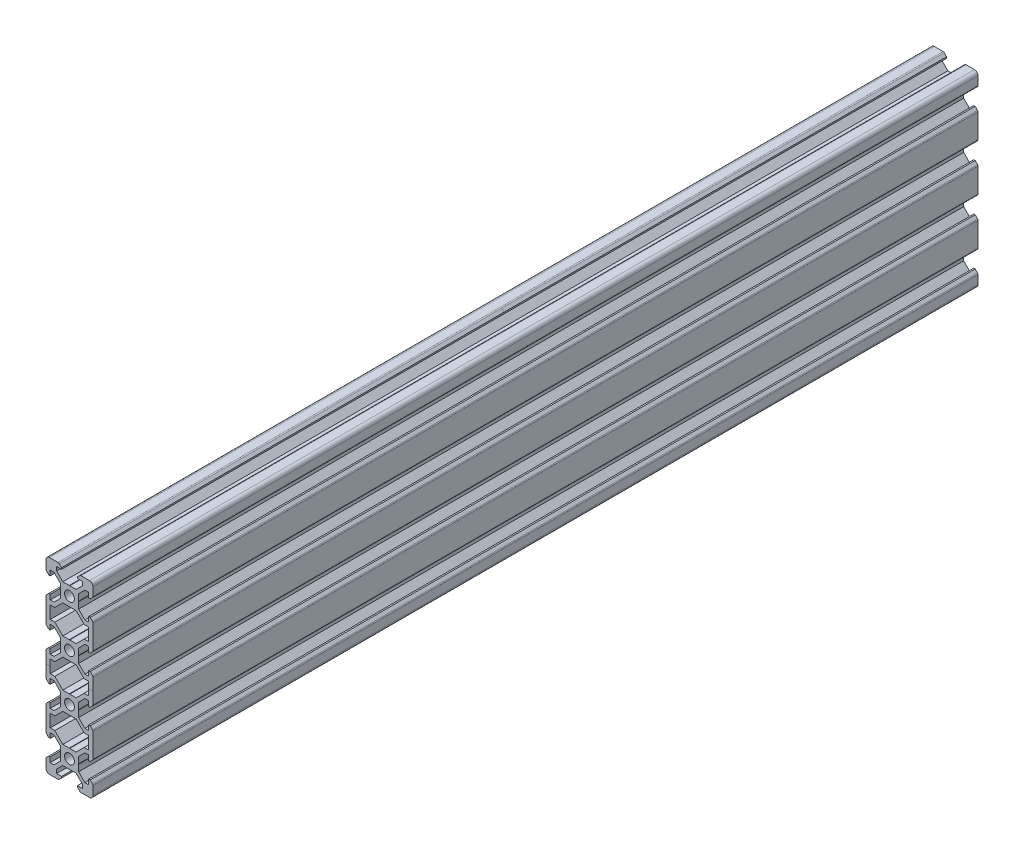
SolidWorks part; units mm, degrees
material "6063-T5"
ref_plane "Front" through (0, 0, 0) normal (0, 0, 1) x (1, 0, 0)
ref_plane "Top" through (0, 0, 0) normal (0, 1, 0) x (1, 0, 0)
ref_plane "Right" through (0, 0, 0) normal (1, 0, 0) x (0, 0, -1)
sketch "Sketch1" plane through (0, 0, 0) normal (0, 0, 1) x (1, 0, 0)
  line L0 (-8.5, 10) -> (-10, 8.5) construction
  line L1 (-8.5, 10) -> (-4.8628, 10)
  line L2 (-10, 8.5) -> (-10, 4.8628)
  line L3 (25.9287, -20) -> (-28.3599, -20) construction
  line L4 (10, 8.5) -> (10, 4.8628)
  line L5 (-10, 10) -> (10, -10) construction
  line L6 (-10, -10) -> (10, 10) construction
  line L7 (8.2, -5.5) -> (8.2, -3.3865)
  line L8 (-8.2, -5.5) -> (-8.2, -3.3865)
  line L9 (-5.5, 8.2) -> (-3.3865, 8.2)
  line L10 (-8.2, -12.7) -> (-8.2, -7.3)
  line L11 (-3.9005, 2.8395) -> (-6.561, 5.5)
  line L12 (-6.561, 5.5) -> (-8.2, 5.5)
  line L13 (-2.8395, -3.9005) -> (-0.1, -3.9005)
  line L14 (-3.9005, -2.8395) -> (-3.9005, -0.1)
  line L15 (-2.8395, 3.9005) -> (-0.1, 3.9005)
  line L16 (3.9005, -2.8395) -> (3.9005, -0.1)
  line L17 (-8.2, 3.3865) -> (-8.81, 3.3865)
  line L18 (-8.81, 3.3865) -> (-9.7976, 4.3741)
  line L19 (8.5, 10) -> (10, 8.5) construction
  line L20 (-2.8395, 3.9005) -> (-5.5, 6.561)
  line L21 (-5.5, 6.561) -> (-5.5, 8.2)
  line L22 (-3.3865, 8.2) -> (-3.3865, 8.81)
  line L23 (-3.3865, 8.81) -> (-4.3741, 9.7976)
  line L24 (0, 24.069) -> (0, -33.8154) construction
  line L25 (3.3865, 8.81) -> (4.3741, 9.7976)
  line L26 (3.3865, 8.2) -> (3.3865, 8.81)
  line L27 (5.5, 6.561) -> (5.5, 8.2)
  line L28 (2.8395, 3.9005) -> (5.5, 6.561)
  line L29 (3.3865, 8.2) -> (5.5, 8.2)
  line L30 (4.8628, 10) -> (8.5, 10)
  line L31 (-0.1, 3.9005) -> (0, 3.8005)
  line L32 (0.1, 3.9005) -> (0, 3.8005)
  line L33 (0.1, 3.9005) -> (2.8395, 3.9005)
  line L34 (25.9287, 0) -> (-28.3459, 0) construction
  line L35 (-0.1, -3.9005) -> (0, -3.8005)
  line L36 (0.1, -3.9005) -> (0, -3.8005)
  line L37 (0.1, -3.9005) -> (2.8395, -3.9005)
  line L38 (-3.9005, 0.1) -> (-3.8005, 0)
  line L39 (-3.8005, 0) -> (-3.9005, -0.1)
  line L40 (-3.9005, 0.1) -> (-3.9005, 2.8395)
  line L41 (3.9005, 0.1) -> (3.8005, 0)
  line L42 (3.8005, 0) -> (3.9005, -0.1)
  line L43 (3.9005, 0.1) -> (3.9005, 2.8395)
  line L44 (8.81, 3.3865) -> (9.7976, 4.3741)
  line L45 (8.2, 3.3865) -> (8.81, 3.3865)
  line L46 (6.561, 5.5) -> (8.2, 5.5)
  line L47 (3.9005, 2.8395) -> (6.561, 5.5)
  line L48 (2.8395, -3.9005) -> (5.5, -6.561)
  line L49 (3.9005, -2.8395) -> (6.561, -5.5)
  line L50 (-2.8395, -3.9005) -> (-5.5, -6.561)
  line L51 (-3.9005, -2.8395) -> (-6.561, -5.5)
  line L52 (6.561, -5.5) -> (8.2, -5.5)
  line L53 (-6.561, -5.5) -> (-8.2, -5.5)
  line L54 (-8.81, -3.3865) -> (-9.7976, -4.3741)
  line L55 (-8.2, -3.3865) -> (-8.81, -3.3865)
  line L56 (8.81, -3.3865) -> (9.7976, -4.3741)
  line L57 (8.2, -3.3865) -> (8.81, -3.3865)
  line L58 (8.2, 3.3865) -> (8.2, 5.5)
  line L59 (10, -4.8628) -> (10, -15.1372)
  line L60 (-8.2, 3.3865) -> (-8.2, 5.5)
  line L61 (-10, -4.8628) -> (-10, -15.1372)
  line L62 (-28.3459, -10) -> (-10, -10) construction
  line L63 (-3.9005, -20.1) -> (-3.9005, -22.8395)
  line L64 (-3.9005, -20.1) -> (-3.8005, -20)
  line L65 (-3.8005, -20) -> (-3.9005, -19.9)
  line L66 (3.9005, -20.1) -> (3.9005, -22.8395)
  line L67 (3.9005, -20.1) -> (3.8005, -20)
  line L68 (3.8005, -20) -> (3.9005, -19.9)
  line L69 (6.561, -14.5) -> (8.2, -14.5)
  line L70 (3.9005, -17.1605) -> (6.561, -14.5)
  line L71 (3.9005, -17.1605) -> (3.9005, -19.9)
  line L72 (-3.9005, -17.1605) -> (-3.9005, -19.9)
  line L73 (-3.9005, -17.1605) -> (-6.561, -14.5)
  line L74 (-6.561, -14.5) -> (-8.2, -14.5)
  line L75 (-8.2, -16.6135) -> (-8.81, -16.6135)
  line L76 (-8.81, -16.6135) -> (-9.7976, -15.6259)
  line L77 (8.2, -16.6135) -> (8.81, -16.6135)
  line L78 (8.81, -16.6135) -> (9.7976, -15.6259)
  line L79 (-2.8395, -16.0995) -> (-5.5, -13.439)
  line L80 (-2.8395, -16.0995) -> (-0.1, -16.0995)
  line L81 (-0.1, -16.0995) -> (0, -16.1995)
  line L82 (0.1, -16.0995) -> (0, -16.1995)
  line L83 (0.1, -16.0995) -> (2.8395, -16.0995)
  line L84 (2.8395, -16.0995) -> (5.5, -13.439)
  line L85 (-8.2, -16.6135) -> (-8.2, -14.5)
  line L86 (8.2, -16.6135) -> (8.2, -14.5)
  line L87 (2.8395, -23.9005) -> (5.5, -26.561)
  line L88 (-2.8395, -23.9005) -> (-5.5, -26.561)
  line L89 (-0.1, -23.9005) -> (0, -23.8005)
  line L90 (0.1, -23.9005) -> (0, -23.8005)
  line L91 (0.1, -23.9005) -> (2.8395, -23.9005)
  line L92 (-2.8395, -23.9005) -> (-0.1, -23.9005)
  line L93 (-8.2, -23.3865) -> (-8.2, -25.5)
  line L94 (-8.2, -23.3865) -> (-8.81, -23.3865)
  line L95 (-8.81, -23.3865) -> (-9.7976, -24.3741)
  line L96 (8.2, -23.3865) -> (8.2, -25.5)
  line L97 (8.2, -23.3865) -> (8.81, -23.3865)
  line L98 (8.81, -23.3865) -> (9.7976, -24.3741)
  line L99 (8.2, -27.3) -> (8.2, -32.7)
  line L100 (10, -35.1372) -> (10, -24.8628)
  line L101 (-10, -35.1372) -> (-10, -24.8628)
  line L102 (-8.2, -27.3) -> (-8.2, -32.7)
  line L103 (3.9005, -22.8395) -> (6.561, -25.5)
  line L104 (-3.9005, -22.8395) -> (-6.561, -25.5)
  line L105 (6.239, -27.3) -> (8.2, -27.3)
  line L106 (-6.239, -27.3) -> (-8.2, -27.3)
  line L107 (-6.561, -25.5) -> (-8.2, -25.5)
  line L108 (6.561, -25.5) -> (8.2, -25.5)
  line L109 (5.5, -26.561) -> (6.239, -27.3)
  line L110 (-5.5, -26.561) -> (-6.239, -27.3)
  line L111 (8.2, -34.5) -> (8.2, -36.6135)
  line L112 (8.2, -36.6135) -> (8.81, -36.6135)
  line L113 (8.81, -36.6135) -> (9.7976, -35.6259)
  line L114 (-8.2, -34.5) -> (-8.2, -36.6135)
  line L115 (-6.239, -7.3) -> (-8.2, -7.3)
  line L116 (-5.5, -6.561) -> (-6.239, -7.3)
  line L117 (6.239, -7.3) -> (8.2, -7.3)
  line L118 (5.5, -6.561) -> (6.239, -7.3)
  line L119 (-6.239, -12.7) -> (-8.2, -12.7)
  line L120 (-5.5, -13.439) -> (-6.239, -12.7)
  line L121 (5.5, -13.439) -> (6.239, -12.7)
  line L122 (6.239, -12.7) -> (8.2, -12.7)
  line L123 (8.2, -12.7) -> (8.2, -7.3)
  line L124 (-8.2, -36.6135) -> (-8.81, -36.6135)
  line L125 (10, -10) -> (25.9287, -10) construction
  line L126 (-8.81, -36.6135) -> (-9.7976, -35.6259)
  line L127 (-0.1, -56.0995) -> (0, -56.1995)
  line L128 (-0.1, -36.0995) -> (0, -36.1995)
  line L129 (0.1, -36.0995) -> (0, -36.1995)
  line L130 (0.1, -36.0995) -> (2.8395, -36.0995)
  line L131 (-6.561, -34.5) -> (-8.2, -34.5)
  line L132 (6.561, -34.5) -> (8.2, -34.5)
  line L133 (6.239, -32.7) -> (8.2, -32.7)
  line L134 (-6.239, -32.7) -> (-8.2, -32.7)
  line L135 (-5.5, -33.439) -> (-6.239, -32.7)
  line L136 (5.5, -33.439) -> (6.239, -32.7)
  line L137 (-26.6965, -30) -> (27.5921, -30) construction
  line L138 (0.1, -56.0995) -> (0, -56.1995)
  line L139 (0.1, -56.0995) -> (2.8395, -56.0995)
  line L140 (-2.8395, -56.0995) -> (-0.1, -56.0995)
  line L141 (0, -60) -> (0, -71.7864) construction
  line L142 (-3.8005, -60) -> (-3.9005, -59.9)
  line L143 (-3.9005, -60.1) -> (-3.8005, -60)
  line L144 (10, -68.5) -> (10, -64.8628)
  line L145 (0.1, -63.9005) -> (0, -63.8005)
  line L146 (-0.1, -63.9005) -> (0, -63.8005)
  line L147 (-2.8395, -63.9005) -> (-0.1, -63.9005)
  line L148 (0.1, -63.9005) -> (2.8395, -63.9005)
  line L149 (3.9005, -60.1) -> (3.9005, -62.8395)
  line L150 (3.9005, -60.1) -> (3.8005, -60)
  line L151 (3.8005, -60) -> (3.9005, -59.9)
  line L152 (3.9005, -57.1605) -> (3.9005, -59.9)
  line L153 (4.8628, -70) -> (8.5, -70)
  line L154 (3.3865, -68.81) -> (4.3741, -69.7976)
  line L155 (3.3865, -68.2) -> (3.3865, -68.81)
  line L156 (3.3865, -68.2) -> (5.5, -68.2)
  line L157 (-0.1, -43.9005) -> (0, -43.8005)
  line L158 (0.1, -43.9005) -> (0, -43.8005)
  line L159 (-2.8395, -43.9005) -> (-0.1, -43.9005)
  line L160 (0.1, -43.9005) -> (2.8395, -43.9005)
  line L161 (3.9005, -40.1) -> (3.8005, -40)
  line L162 (3.8005, -40) -> (3.9005, -39.9)
  line L163 (3.9005, -37.1605) -> (3.9005, -39.9)
  line L164 (3.9005, -40.1) -> (3.9005, -42.8395)
  line L165 (-2.8395, -36.0995) -> (-0.1, -36.0995)
  line L166 (-2.8395, -43.9005) -> (-5.5, -46.561)
  line L167 (-3.9005, -37.1605) -> (-3.9005, -39.9)
  line L168 (-3.8005, -40) -> (-3.9005, -39.9)
  line L169 (-3.9005, -40.1) -> (-3.8005, -40)
  line L170 (-3.9005, -42.8395) -> (-6.561, -45.5)
  line L171 (2.8395, -43.9005) -> (5.5, -46.561)
  line L172 (3.9005, -42.8395) -> (6.561, -45.5)
  line L173 (3.9005, -37.1605) -> (6.561, -34.5)
  line L174 (2.8395, -36.0995) -> (5.5, -33.439)
  line L175 (-3.9005, -42.8395) -> (-3.9005, -40.1)
  line L176 (-6.561, -34.5) -> (-3.9005, -37.1605)
  line L177 (-5.5, -33.439) -> (-2.8395, -36.0995)
  line L178 (5.5, -66.561) -> (5.5, -68.2)
  line L179 (6.561, -65.5) -> (8.2, -65.5)
  line L180 (8.2, -63.3865) -> (8.2, -65.5)
  line L181 (8.81, -63.3865) -> (9.7976, -64.3741)
  line L182 (8.2, -63.3865) -> (8.81, -63.3865)
  line L183 (-8.2, -63.3865) -> (-8.81, -63.3865)
  line L184 (-8.81, -63.3865) -> (-9.7976, -64.3741)
  line L185 (-8.2, -63.3865) -> (-8.2, -65.5)
  line L186 (-6.561, -65.5) -> (-8.2, -65.5)
  line L187 (-5.5, -66.561) -> (-5.5, -68.2)
  line L188 (-5.5, -68.2) -> (-3.3865, -68.2)
  line L189 (-3.3865, -68.2) -> (-3.3865, -68.81)
  line L190 (-3.3865, -68.81) -> (-4.3741, -69.7976)
  line L191 (-10, -68.5) -> (-10, -64.8628)
  line L192 (-8.5, -70) -> (-4.8628, -70)
  line L193 (-8.2, -43.3865) -> (-8.81, -43.3865)
  line L194 (-8.81, -43.3865) -> (-9.7976, -44.3741)
  line L195 (-10, -55.1372) -> (-10, -44.8628)
  line L196 (-8.81, -56.6135) -> (-9.7976, -55.6259)
  line L197 (-8.2, -56.6135) -> (-8.81, -56.6135)
  line L198 (8.2, -56.6135) -> (8.81, -56.6135)
  line L199 (8.81, -56.6135) -> (9.7976, -55.6259)
  line L200 (8.2, -43.3865) -> (8.81, -43.3865)
  line L201 (8.81, -43.3865) -> (9.7976, -44.3741)
  line L202 (10, -55.1372) -> (10, -44.8628)
  line L203 (-8.2, -47.3) -> (-8.2, -52.7)
  line L204 (8.2, -47.3) -> (8.2, -52.7)
  line L205 (-6.239, -52.7) -> (-8.2, -52.7)
  line L206 (6.239, -52.7) -> (8.2, -52.7)
  line L207 (-6.561, -54.5) -> (-8.2, -54.5)
  line L208 (6.561, -54.5) -> (8.2, -54.5)
  line L209 (-3.9005, -60.1) -> (-3.9005, -62.8395)
  line L210 (-2.8395, -56.0995) -> (-5.5, -53.439)
  line L211 (3.9005, -57.1605) -> (6.561, -54.5)
  line L212 (2.8395, -56.0995) -> (5.5, -53.439)
  line L213 (5.5, -53.439) -> (6.239, -52.7)
  line L214 (-5.5, -53.439) -> (-6.239, -52.7)
  line L215 (-8.2, -43.3865) -> (-8.2, -45.5)
  line L216 (8.2, -43.3865) -> (8.2, -45.5)
  line L217 (-2.8395, -63.9005) -> (-5.5, -66.561)
  line L218 (-3.9005, -62.8395) -> (-6.561, -65.5)
  line L219 (2.8395, -63.9005) -> (5.5, -66.561)
  line L220 (3.9005, -62.8395) -> (6.561, -65.5)
  line L221 (-8.2, -54.5) -> (-8.2, -56.6135)
  line L222 (8.2, -54.5) -> (8.2, -56.6135)
  line L223 (6.239, -47.3) -> (8.2, -47.3)
  line L224 (-6.239, -47.3) -> (-8.2, -47.3)
  line L225 (-6.561, -45.5) -> (-8.2, -45.5)
  line L226 (-5.5, -46.561) -> (-6.239, -47.3)
  line L227 (6.561, -45.5) -> (8.2, -45.5)
  line L228 (5.5, -46.561) -> (6.239, -47.3)
  line L229 (-3.9005, -57.1605) -> (-3.9005, -59.9)
  line L230 (-3.9005, -57.1605) -> (-6.561, -54.5)
  circle A0 centre (0, 0) radius 2.1
  arc A1 (-8.5, 10) -> (-10, 8.5) centre (-8.5, 8.5) ccw
  arc A2 (10, 8.5) -> (8.5, 10) centre (8.5, 8.5) ccw
  arc A3 (-4.3741, 9.7976) -> (-4.8628, 10) centre (-4.8628, 9.3088) ccw
  arc A4 (4.8628, 10) -> (4.3741, 9.7976) centre (4.8628, 9.3088) ccw
  circle A5 centre (0, -20) radius 2.1
  arc A6 (9.7976, 4.3741) -> (10, 4.8628) centre (9.3088, 4.8628) ccw
  arc A7 (-10, 4.8628) -> (-9.7976, 4.3741) centre (-9.3088, 4.8628) ccw
  arc A8 (-10, -4.8628) -> (-9.7976, -4.3741) centre (-9.3088, -4.8628) cw
  arc A9 (9.7976, -4.3741) -> (10, -4.8628) centre (9.3088, -4.8628) cw
  arc A10 (-10, -15.1372) -> (-9.7976, -15.6259) centre (-9.3088, -15.1372) ccw
  arc A11 (9.7976, -15.6259) -> (10, -15.1372) centre (9.3088, -15.1372) ccw
  arc A12 (-10, -24.8628) -> (-9.7976, -24.3741) centre (-9.3088, -24.8628) cw
  arc A13 (9.7976, -24.3741) -> (10, -24.8628) centre (9.3088, -24.8628) cw
  arc A14 (9.7976, -35.6259) -> (10, -35.1372) centre (9.3088, -35.1372) ccw
  arc A15 (-10, -35.1372) -> (-9.7976, -35.6259) centre (-9.3088, -35.1372) ccw
  circle A16 centre (0, -40) radius 2.1
  circle A17 centre (0, -60) radius 2.1
  arc A18 (10, -68.5) -> (8.5, -70) centre (8.5, -68.5) cw
  arc A19 (4.8628, -70) -> (4.3741, -69.7976) centre (4.8628, -69.3088) cw
  arc A20 (9.7976, -64.3741) -> (10, -64.8628) centre (9.3088, -64.8628) cw
  arc A21 (-10, -64.8628) -> (-9.7976, -64.3741) centre (-9.3088, -64.8628) cw
  arc A22 (-4.3741, -69.7976) -> (-4.8628, -70) centre (-4.8628, -69.3088) cw
  arc A23 (-8.5, -70) -> (-10, -68.5) centre (-8.5, -68.5) cw
  arc A24 (-10, -44.8628) -> (-9.7976, -44.3741) centre (-9.3088, -44.8628) cw
  arc A25 (-10, -55.1372) -> (-9.7976, -55.6259) centre (-9.3088, -55.1372) ccw
  arc A26 (9.7976, -55.6259) -> (10, -55.1372) centre (9.3088, -55.1372) ccw
  arc A27 (9.7976, -44.3741) -> (10, -44.8628) centre (9.3088, -44.8628) cw
  point P17 (-9.25, 9.25)
  point P21 (9.25, 9.25)
  point P181 (-10, -30)
  dimension "D2" = 4.2
  dimension "D4" = 1.5
  dimension "D3" = 20
  dimension "D5" = 0.529
  dimension "D6" = 6.773
  dimension "D7" = 90
  dimension "D8" = 11
  dimension "D9" = 0.61
  dimension "D10" = 0.1
  dimension "D11" = 0.1
  dimension "D12" = 0.1
  dimension "D13" = 0.1
  dimension "D14" = 5.679
  dimension "D15" = 1.639
  dimension "D16" = 1.8
  dimension "D17" = 90
  dimension "D18" = 6.773
  dimension "D19" = 90
  dimension "D20" = 20
  dimension "D21" = 1.8
extrude "Boss-Extrude2" add sketch "Sketch1" along normal blind 377
sketch "Sketch2" plane through (0, 0, 377) normal (0, 0, 1) x (1, 0, 0)
  line L0 (-10, -30) -> (10, -30)
  line L1 (-10, -24.8628) -> (-10, -35.1372) construction
  line L2 (10, -35.1372) -> (10, -24.8628) construction
split line "SideFixture1 - SplitLine"
sketch "Sketch3" plane through (0, 0, 0) normal (0, 0, -1) x (-1, 0, 0)
  line L0 (-10, -30) -> (10, -30)
  line L1 (-10, -35.1372) -> (-10, -24.8628) construction
  line L2 (10, -24.8628) -> (10, -35.1372) construction
split line "SideFixture2 - SplitLine"
sketch "Sketch4" plane through (0, 10, 0) normal (0, 1, 0) x (1, 0, 0)
  line L0 (8.5, -188.5) -> (-8.5, -188.5)
  line L1 (8.5, -377) -> (8.5, 0) construction
  line L2 (-8.5, -377) -> (-8.5, 0) construction
split line "SideFixture3 - SplitLine"
equation "\"base-xwidth\"= 455mm"
equation "\"base-yheight\"= 500mm"
equation "\"base-zdepth\" = 377mm"
equation "\"D1@Boss-Extrude2\"=\"base-zdepth\""
